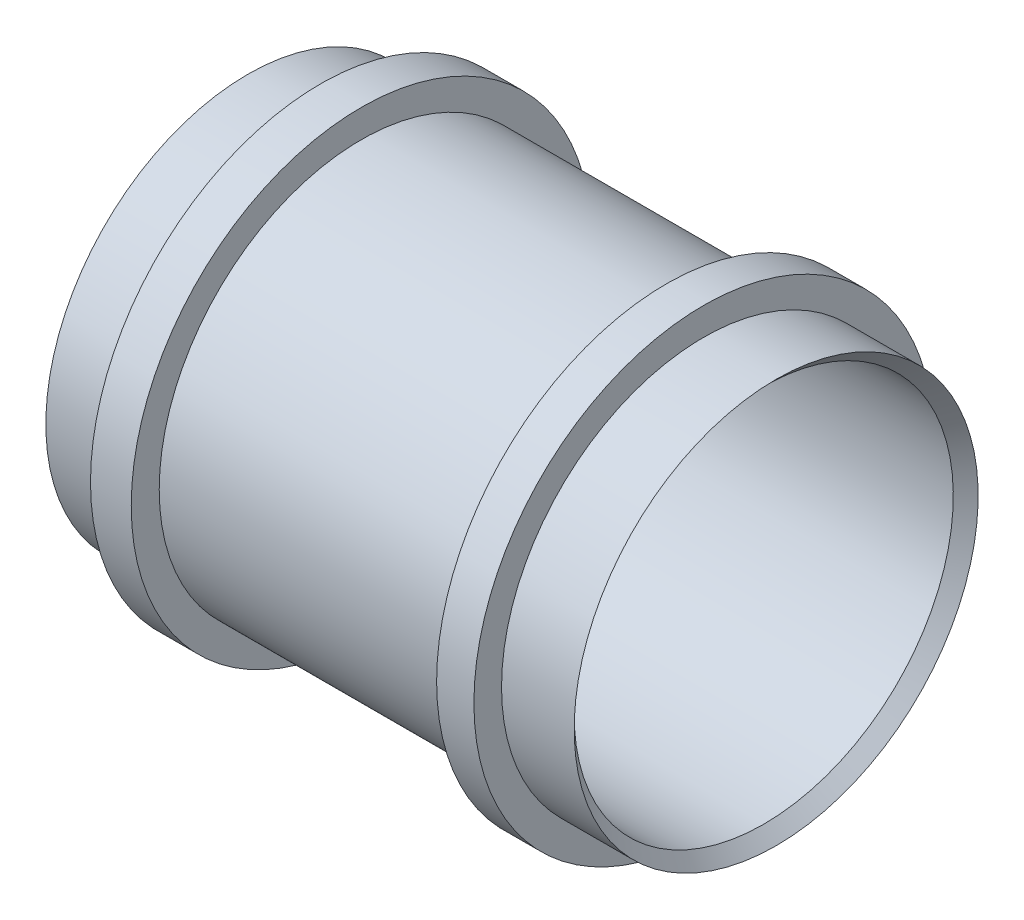
SolidWorks part; units mm, degrees
ref_plane "Front Plane" through (0, 0, 0) normal (0, 0, 1) x (1, 0, 0)
ref_plane "Top Plane" through (0, 0, 0) normal (0, 1, 0) x (1, 0, 0)
ref_plane "Right Plane" through (0, 0, 0) normal (1, 0, 0) x (0, 0, -1)
sketch "Sketch1" plane through (0, 0, 0) normal (0, 0, 1) x (1, 0, 0)
  line L0 (-117.087, 0) -> (52.913, 0) construction
  line L1 (-117.087, 65) -> (-112.3139, 60.2269)
  line L2 (-117.087, 65) -> (52.913, 65)
  line L3 (-112.3139, 60.2269) -> (48.913, 61)
  line L10 (52.913, 65) -> (48.913, 61)
  line L11 (-113.087, 61) -> (48.913, 61)
  line L13 (-117.087, 0) -> (-117.087, 65) construction
  line L14 (-113.087, 0) -> (-113.087, 61) construction
  line L15 (48.913, 61) -> (48.913, 0) construction
  line L16 (52.913, 65) -> (52.913, 0) construction
  point P3 (0, 0)
  point P6 (0, 0)
  dimension "D1" = 65
  dimension "D2" = 170
  dimension "D3" = 65
  dimension "D7" = 4
revolve "Revolve2" add sketch "Sketch1" angle 360 about L0
sketch "Sketch9" plane through (0, 0, 0) normal (0, 0, 1) x (1, 0, 0)
  line L0 (-161.5495, 0) -> (93.6299, 0) construction
  line L1 (-93.719, 65) -> (-93.719, 74)
  line L2 (52.913, 65) -> (-117.087, 65) construction
  line L3 (-93.719, 74) -> (-80.6063, 74)
  line L4 (-80.6063, 74) -> (-80.6063, 65)
  line L5 (-93.719, 65) -> (-80.6063, 65)
  dimension "D1" = 9
  dimension "D5" = 23.368
  dimension "D6" = 13.1128
revolve "Revolve4" add sketch "Sketch9" angle 360 about L0
sketch "Sketch11" plane through (0, 0, 0) normal (0, 0, 1) x (1, 0, 0)
  line L0 (-147.7452, 0) -> (101.0446, 0) construction
  line L1 (29.545, 65) -> (17.545, 65)
  line L2 (52.913, 65) -> (-80.6063, 65) construction
  line L3 (29.545, 65) -> (29.545, 73.89)
  line L4 (29.545, 73.89) -> (17.545, 73.89)
  line L5 (17.545, 73.89) -> (17.545, 65)
  point P3 (0, 0)
  dimension "D1" = 23.368
  dimension "D2" = 12
  dimension "D3" = 8.89
revolve "Revolve5" add sketch "Sketch11" angle 360 about L0
